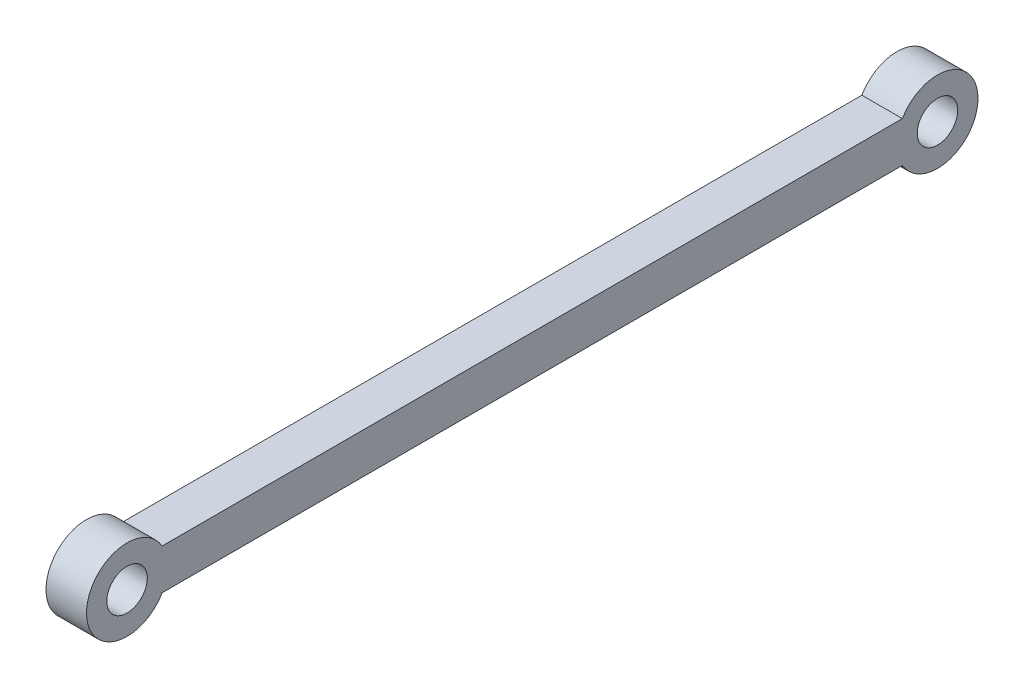
SolidWorks part; units mm, degrees
ref_plane "정면" through (0, 0, 0) normal (0, 0, 1) x (1, 0, 0)
ref_plane "윗면" through (0, 0, 0) normal (0, 1, 0) x (1, 0, 0)
ref_plane "우측면" through (0, 0, 0) normal (1, 0, 0) x (0, 0, -1)
sketch "스케치1" plane through (0, 0, 0) normal (1, 0, 0) x (0, 0, -1)
  line L0 (-25, 0) -> (25, 0) construction
  line L1 (-22.8349, 1.25) -> (22.8349, 1.25)
  line L3 (-22.8349, -1.25) -> (22.8349, -1.25)
  line L5 (0, 1.25) -> (0, -1.25) construction
  arc A0 (-22.8349, 1.25) -> (-22.8349, -1.25) centre (-25, 0) ccw
  circle A1 centre (-25, 0) radius 1.25
  arc A2 (22.8349, -1.25) -> (22.8349, 1.25) centre (25, 0) ccw
  circle A3 centre (25, 0) radius 1.25
  dimension "D3" = 5
  dimension "D4" = 5
  dimension "D1" = 2.5
  dimension "D2" = 50
extrude "보스-돌출1" add sketch "스케치1" along normal blind 2.5
equation "\"link11\" = 80"
equation "\"link12\" = 40"
equation "\"link21\"= 60"
equation "\"link22\"= 40"
equation "\"link31\"= 50"
equation "\"link32\"= 40"
equation "\"link41\"= 40"
equation "\"link42\"= 40"
equation "\"D2@스케치1\"=\"link31\""
